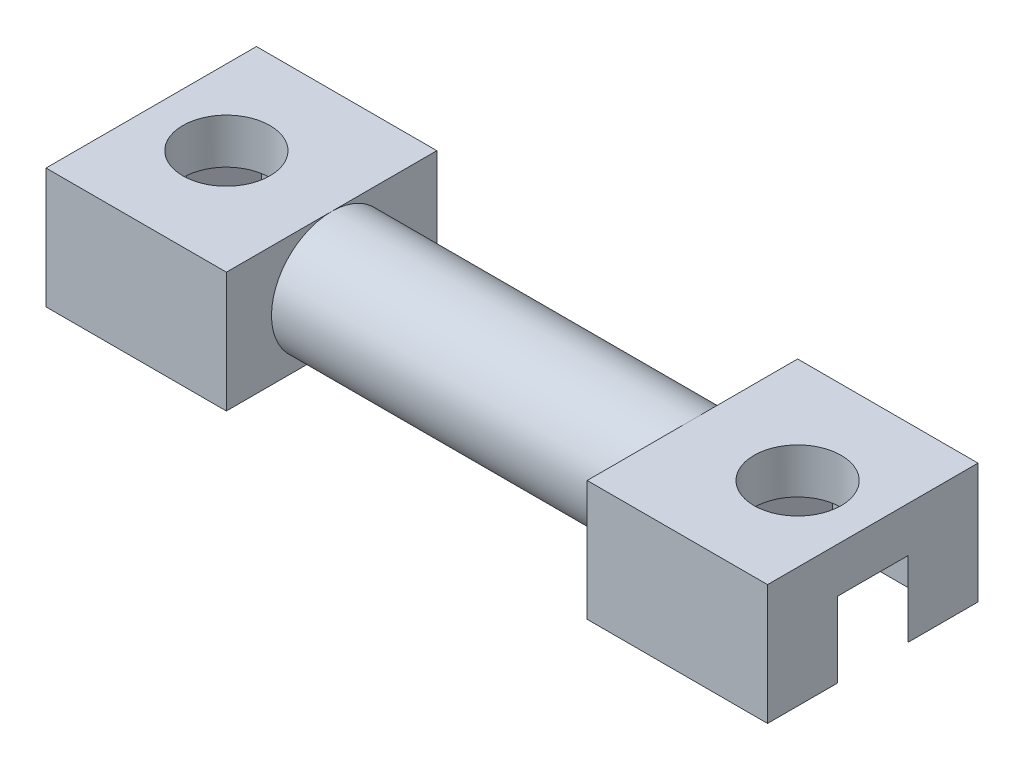
SolidWorks part; units mm, degrees
ref_plane "Спереди" through (0, 0, 0) normal (0, 0, 1) x (1, 0, 0)
ref_plane "Сверху" through (0, 0, 0) normal (0, 1, 0) x (1, 0, 0)
ref_plane "Справа" through (0, 0, 0) normal (1, 0, 0) x (0, 0, -1)
sketch "Эскиз1" plane through (0, 0, 0) normal (0, 1, 0) x (1, 0, 0)
  line L0 (0, -1000) -> (0, 49000) construction
  line L1 (-12, -3.5) -> (12, -3.5)
  line L2 (-12, -3.5) -> (-12, 3.5)
  line L3 (-12, 3.5) -> (12, 3.5)
  line L4 (12, -3.5) -> (12, 3.5)
  line L5 (-12, -3.5) -> (12, 3.5) construction
  line L6 (-12, 3.5) -> (12, -3.5) construction
  circle A0 centre (-9.5, 0) radius 1.45
  circle A1 centre (9.5, 0) radius 1.45
  point P0 (0, 0)
  dimension "D1" = 19
  dimension "D2" = 2.9
  dimension "D3" = 7
  dimension "D4" = 24
extrude "Бобышка-Вытянуть1" add sketch "Эскиз1" along normal blind 4
sketch "Эскиз2" plane through (0, 0, 0) normal (0, -1, 0) x (1, 0, 0)
  line L1 (-7.9123, 2.75) -> (-11.0877, 2.75)
  line L2 (-11.0877, 2.75) -> (-12.6754, 0)
  line L3 (-12.6754, 0) -> (-11.0877, -2.75)
  line L4 (-11.0877, -2.75) -> (-7.9123, -2.75)
  line L5 (-7.9123, -2.75) -> (-6.3246, 0)
  line L6 (-6.3246, 0) -> (-7.9123, 2.75)
  line L7 (7.9123, -2.75) -> (11.0877, -2.75)
  line L8 (11.0877, -2.75) -> (12.6754, 0)
  line L9 (12.6754, 0) -> (11.0877, 2.75)
  line L10 (11.0877, 2.75) -> (7.9123, 2.75)
  line L11 (7.9123, 2.75) -> (6.3246, 0)
  line L12 (6.3246, 0) -> (7.9123, -2.75)
  circle A0 centre (-9.5, 0) radius 2.75 construction
  circle A1 centre (-9.5, 0) radius 1.45 construction
  circle A2 centre (9.5, 0) radius 2.75 construction
  dimension "D1" = 5.5
extrude "Вырез-Вытянуть1" cut sketch "Эскиз2" against normal blind 2.5
sketch "Эскиз3" plane through (0, 0, 0) normal (1, 0, 0) x (0, 0, -1)
  line L0 (0, 2.5) -> (0, 0) construction
  line L1 (1.1699, 0) -> (3.5, 0) construction
  line L2 (-3.9044, 4.4642) -> (4.2813, 4.4642)
  line L3 (-3.9044, 4.4642) -> (-3.9044, -0.6918)
  line L4 (-3.9044, -0.6918) -> (4.2813, -0.6918)
  line L5 (4.2813, 4.4642) -> (4.2813, -0.6918)
  line L6 (-3.5, 4) -> (3.5, 4) construction
  circle A0 centre (0, 2) radius 2
  dimension "D1" = 2
extrude "Вырез-Вытянуть2" cut sketch "Эскиз3" against normal mid plane 12
